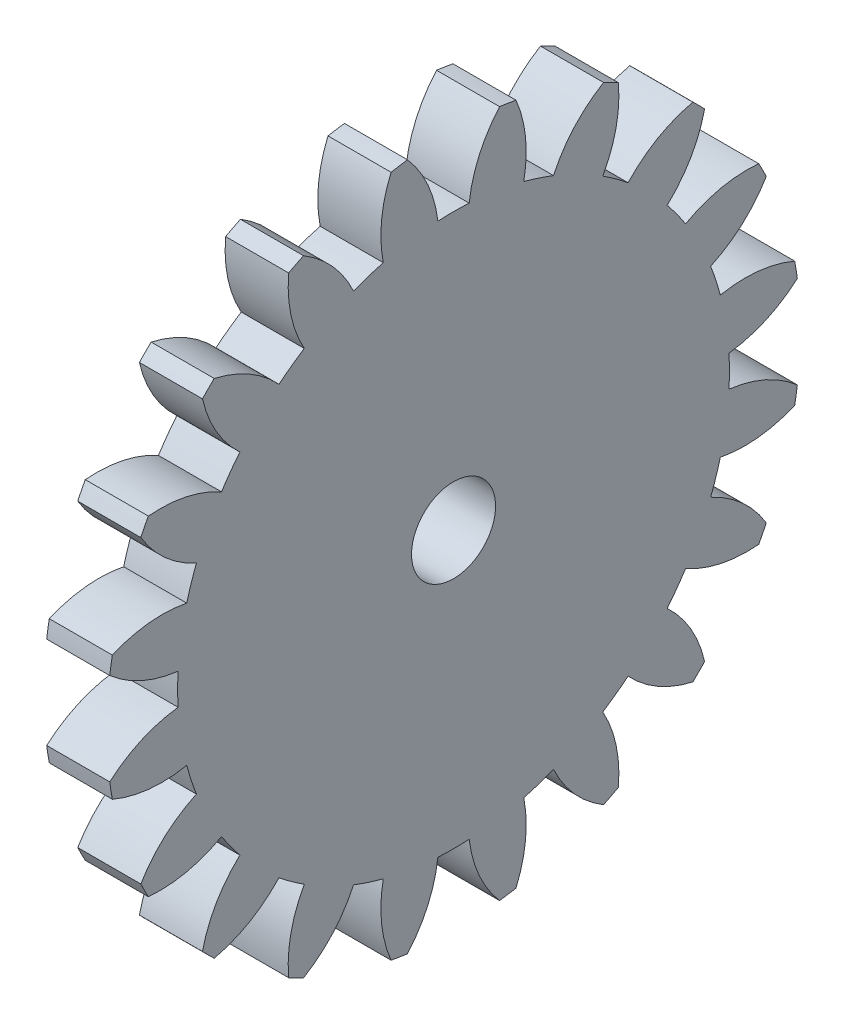
SolidWorks part; units mm, degrees
ref_plane "Plane1" through (0, 0, 0) normal (0, 0, 1) x (1, 0, 0)
ref_plane "Plane2" through (0, 0, 0) normal (0, 1, 0) x (1, 0, 0)
ref_plane "Plane3" through (0, 0, 0) normal (1, 0, 0) x (0, 0, -1)
other "Configuration Table"
sketch "HoldingSke" plane through (0, 0, 0) normal (0, 1, 0) x (1, 0, 0)
  line L0 (0, 0) -> (0.6265, -0.228)
  line L1 (-15, 0) -> (100, 0) construction
  line L2 (0, 0) -> (-2.1039, 2.3779)
  line L3 (0, 0) -> (-11.863, 4.5341)
  line L4 (0, 0) -> (8.1152, 2.9537)
  line L5 (0, 0) -> (-46.8476, -17.4728)
  line L6 (0, 0) -> (-2.4869, -1.6779)
  line L7 (-2.1039, 2.3779) -> (8.6586, 51.2059)
  line L8 (-76.2, 54.61) -> (-75.5, 54.61)
  line L9 (-71.009, 38.7566) -> (-53.1078, 45.2721)
  line L10 (-76.2, 71.12) -> (104.1128, 71.12)
  line L11 (0, 0) -> (-3, 0)
  line L12 (-76.2, 101.6) -> (-76.147, 101.6)
  line L13 (24.9733, 27.94) -> (52.9518, 28.4284)
  line L14 (24.9733, 27.94) -> (24.9743, 27.94)
  line L15 (24.9733, 27.94) -> (100.4006, 29.5858)
  line L16 (-63.627, -1.5) -> (-12.827, -1.5)
  circle A0 centre (0, 0) radius 2
  circle A1 centre (0, 0) radius 13.124
  circle A2 centre (0, 0) radius 37.5
  circle A3 centre (0, 0) radius 2
  dimension "MHD" = 26.248
  dimension "Hub_dia" = 75
  dimension "Bore" = 4
  dimension "MBD" = 4
  dimension "Num_teeth" = 20
  dimension "Pitch" = 0.6667
  dimension "Overall_len" = 50
  dimension "Show_teeth" = 20
  dimension "Thickness" = 3
  dimension "OAL" = 50.0001
  dimension "T_dim" = 0.7
  dimension "Ap" = 20
  dimension "H" = 19.05
  dimension "Pitch_radius" = 180.3128
  dimension "Width" = 3
  dimension "Backlash" = 0.053
  dimension "Addendum_fac" = 1
  dimension "Dedendum_fac" = 1.25
  dimension "Clearance_fac" = 0.25
  dimension "Dedendum_add" = 0.001
  dimension "Module" = 1.5
sketch "BasProSke" plane through (0, 0, 0) normal (0, 1, 0) x (1, 0, 0)
  line L0 (-10, 0) -> (60, 0) construction
  line L1 (0, 0) -> (0, 16.5)
  line L2 (0, 0) -> (3, 0)
  line L3 (3, 0) -> (3, 16.5)
  line L4 (3, 16.5) -> (0, 16.5)
  dimension "Thickness" = 3
  dimension "Diameter" = 33
revolve "Base-Revolve" add sketch "BasProSke" angle 360 about L0
sketch "TooCutSke" plane through (0, 0, 0) normal (1, 0, 0) x (0, 0, -1)
  line L1 (0, 0) -> (0, 107) construction
  line L2 (0, 0) -> (-1.2696, 14.9462) construction
  line L3 (0, 0) -> (-4.6808, 29.5532) construction
  line L4 (-1.2696, 14.9462) -> (-2.3404, 14.7766) construction
  arc A0 (0.7438, 13.1029) -> (-0.7438, 13.1029) centre (0, 0) ccw
  arc A1 (2.21, 16.377) -> (-2.21, 16.377) centre (0, 0) ccw
  circle A2 centre (0, 0) radius 15 construction
  circle A3 centre (0, 0) radius 14.0954 construction
  arc A4 (-0.7438, 13.1029) -> (-2.21, 16.377) centre (-6.7025, 12.3999) ccw
  arc A5 (2.21, 16.377) -> (0.7438, 13.1029) centre (6.7025, 12.3999) ccw
  dimension "Root_dia" = 26.248
  dimension "Overcut_dia" = 33.0508
  dimension "Pitch_dia" = 30
  dimension "Base_dia" = 28.1908
  dimension "Flank_rad" = 6
  dimension "Half_ang" = 9
  dimension "Half_CT" = 1.0841
extrude "ToothCut" cut sketch "TooCutSke" along normal through all
fillet "Breaks" [suppressed] radius 0.03
fillet "RootFillets" [suppressed] radius 0.376
pattern_circular "TeethCuts" count 20 every 18 about axis through (-10, 0, 0) along (1, 0, 0) of "ToothCut", "RootFillets", "Breaks"
sketch "HubNeaOneSke" plane through (0, 0, 0) normal (-1, 0, 0) x (0, 0, 1)
  circle A0 centre (0, 0) radius 13.124
  dimension "Diameter" = 26.248
extrude "HubNearOne" [suppressed] add sketch "HubNeaOneSke" along normal blind 47.0001
sketch "HubNeaBotSke" plane through (0, 0, 0) normal (-1, 0, 0) x (0, 0, 1)
  circle A0 centre (0, 0) radius 13.124
  dimension "Diameter" = 26.248
extrude "HubNearBoth" [suppressed] add sketch "HubNeaBotSke" along normal blind 23.5001
ref_plane "FarPln" through (3, 0, 0) normal (1, 0, 0) x (0, 0, -1)
sketch "HubFarSke" plane through (3, 0, 0) normal (1, 0, 0) x (0, 0, -1)
  circle A0 centre (0, 0) radius 13.124
  dimension "Diameter" = 26.248
extrude "HubFar" [suppressed] add sketch "HubFarSke" along normal blind 23.5001
sketch "BorSke" plane through (0, 0, 0) normal (1, 0, 0) x (0, 0, -1)
  circle A0 centre (0, 0) radius 2
  dimension "Diameter" = 4
extrude "Bore" cut sketch "BorSke" along normal mid plane 100.0002
sketch "KeySke" plane through (0, 0, 0) normal (1, 0, 0) x (0, 0, -1)
  line L0 (-0.8, 0) -> (-0.8, 2.7)
  line L1 (-0.8, 2.7) -> (0.8, 2.7)
  line L2 (0.8, 2.7) -> (0.8, 0)
  line L3 (0, 0) -> (0, 34) construction
  line L4 (-0.8, 0) -> (0.8, 0)
  dimension "Offset" = 2.7
  dimension "Width" = 1.6
extrude "Keyway" [suppressed] cut sketch "KeySke" along normal mid plane 100.0002
pattern_circular "Keyway2" [suppressed] count 2 every 90 about axis through (-10, 0, 0) along (1, 0, 0)
equation "' \"Module@HoldingSke\" = 6.35"
equation "' \"Num_teeth@HoldingSke\" = 12"
equation "' \"Ap@HoldingSke\" =  20"
equation "' \"Ap@HoldingSke\" = 20"
equation "' \"Width@HoldingSke\" = 0.5 * 25.4"
equation "' \"Hub_dia@HoldingSke\"= 1 * 25.4"
equation "' \"Hub_dia@HoldingSke\" = 1 * 25.4"
equation "' \"Overall_len@HoldingSke\" = 1.0 * 25.4"
equation "' \"Bore@HoldingSke\" = 0.75 * 25.4"
equation "' \"T_dim@HoldingSke\" = 0.1 * 25.4"
equation "' \"Width@KeySke\" = 0.25 * 25.4"
equation "' \"Show_teeth@HoldingSke\" = 13"
equation "' \"Backlash@HoldingSke\" = 0.009 * 25.4"
equation "' \"Addendum_fac@HoldingSke\" = 1.0"
equation "' \"Dedendum_fac@HoldingSke\" = 1.25"
equation "' \"Dedendum_add@HoldingSke\" = 0.00005 * 25.4"
equation "' \"Clearance_fac@HoldingSke\" = 0.25"
equation "\"Pitch@HoldingSke\" = 1 / \"Module@HoldingSke\""
equation "\"Overcut_dia@TooCutSke\" = (\"Num_teeth@HoldingSke\" + 2 * \"Addendum_fac@HoldingSke\") / \"Pitch@HoldingSke\" + 0.002 * 25.4"
equation "\"Pitch_dia@TooCutSke\" = \"Num_teeth@HoldingSke\" / \"Pitch@HoldingSke\""
equation "\"Base_dia@TooCutSke\" = \"Num_teeth@HoldingSke\" / \"Pitch@HoldingSke\" * cos((\"Ap@HoldingSke\"  * 3.14159265 / 180))"
equation "\"Root_dia@TooCutSke\" = (\"Num_teeth@HoldingSke\" + 2) / \"Pitch@HoldingSke\" - 2 * (\"Addendum_fac@HoldingSke\" + \"Dedendum_fac@HoldingSke\") / \"Pitch@HoldingSke\" - \"Dedendum_add@HoldingSke\" * 2"
equation "\"Half_ang@TooCutSke\" = 180 / \"Num_teeth@HoldingSke\""
equation "\"Half_CT@TooCutSke\" = \"Num_teeth@HoldingSke\" / \"Pitch@HoldingSke\" * sin((3.14159265 / 2 / \"Num_teeth@HoldingSke\")) / 2 - 7 * \"Backlash@HoldingSke\" / 4"
equation "\"Flank_rad@TooCutSke\" = \"Num_teeth@HoldingSke\" / \"Pitch@HoldingSke\" / 5"
equation "\"Radius@RootFillets\" = \"Clearance_fac@HoldingSke\" / \"Pitch@HoldingSke\" + \"Dedendum_add@HoldingSke\""
equation "\"Break_rad@Breaks\" = 0.02 / \"Pitch@HoldingSke\""
equation "\"Thickness@HoldingSke\" = \"Width@HoldingSke\""
equation "\"OAL@HoldingSke\" = \"Thickness@HoldingSke\""
equation "\"MHD@HoldingSke\" = (\"Num_teeth@HoldingSke\" + 2) / \"Pitch@HoldingSke\" - 2 * (\"Addendum_fac@HoldingSke\" + \"Dedendum_fac@HoldingSke\")  / \"Pitch@HoldingSke\" - \"Dedendum_add@HoldingSke\" * 2"
equation "\"MBD@HoldingSke\" = (\"Num_teeth@HoldingSke\" + 2) / \"Pitch@HoldingSke\" - 2 * (\"Addendum_fac@HoldingSke\" + \"Dedendum_fac@HoldingSke\")  / \"Pitch@HoldingSke\" - \"Dedendum_add@HoldingSke\" * 2 - 0.002 * 25.4"
equation "\"MHD@HoldingSke\" = ((sgn( \"MHD@HoldingSke\" - \"Hub_dia@HoldingSke\" )-1)*( \"MHD@HoldingSke\" - \"Hub_dia@HoldingSke\" ))/-2+ \"Hub_dia@HoldingSke\""
equation "\"MBD@HoldingSke\" = ((sgn( \"MBD@HoldingSke\" - \"Bore@HoldingSke\" )-1)*( \"MBD@HoldingSke\" - \"Bore@HoldingSke\" ))/-2+ \"Bore@HoldingSke\""
equation "\"OAL@HoldingSke\" = ((sgn( \"OAL@HoldingSke\" - \"Overall_len@HoldingSke\" )+1)*( \"OAL@HoldingSke\" - \"Overall_len@HoldingSke\" ))/2 + \"Overall_len@HoldingSke\" + 0.000002 * 25.4"
equation "\"Num_teeth@TeethCuts\" = int( \"Show_teeth@HoldingSke\" ) + 1"
equation "\"Num_teeth@TeethCuts\" = ((sgn( \"Num_teeth@TeethCuts\" - \"Num_teeth@HoldingSke\" )-1)*( \"Num_teeth@TeethCuts\" - \"Num_teeth@HoldingSke\" ))/-2+ \"Num_teeth@HoldingSke\""
equation "\"Num_teeth@TeethCuts\" = ((sgn( \"Num_teeth@TeethCuts\" - 2.0)+1)*( \"Num_teeth@TeethCuts\" - 2.0))/2 +2.0"
equation "\"Angle@TeethCuts\" = 360.0 / \"Num_teeth@HoldingSke\""
equation "\"Diameter@BasProSke\" = (\"Num_teeth@HoldingSke\" + 2 * \"Addendum_fac@HoldingSke\") / \"Pitch@HoldingSke\""
equation "\"Thickness@BasProSke\"  = \"Thickness@HoldingSke\""
equation "' \"Fillet_rad@BasProSke\" =  \"Thickness@HoldingSke\" * 0.05"
equation "' \"Fillet_rad@BasProSke\" = \"Thickness@HoldingSke\" * 0.05"
equation "\"MHD@HoldingSke\" = ((sgn( \"MHD@HoldingSke\" - \"Root_dia@TooCutSke\" )-1)*( \"MHD@HoldingSke\" - \"Root_dia@TooCutSke\" ))/-2+ \"Root_dia@TooCutSke\""
equation "\"Diameter@HubNeaOneSke\" = \"MHD@HoldingSke\""
equation "\"Length@HubNearOne\" = \"OAL@HoldingSke\" - \"Thickness@BasProSke\""
equation "\"Diameter@HubNeaBotSke\" = \"MHD@HoldingSke\""
equation "\"Length@HubNearBoth\" = ( \"OAL@HoldingSke\" - \"Thickness@BasProSke\" ) / 2.0"
equation "\"Thickness@FarPln\" = \"Thickness@BasProSke\""
equation "\"Diameter@HubFarSke\" = \"MHD@HoldingSke\""
equation "\"Length@HubFar\" = ( \"OAL@HoldingSke\" - \"Thickness@BasProSke\" ) / 2.0"
equation "\"Diameter@BorSke\" = \"MBD@HoldingSke\""
equation "\"D1@Bore\" = \"OAL@HoldingSke\" * 2.0"
equation "\"D1@Keyway\" = \"OAL@HoldingSke\" * 2.0"
equation "\"Offset@KeySke\" = \"T_dim@HoldingSke\" + \"MBD@HoldingSke\" / 2.0"
